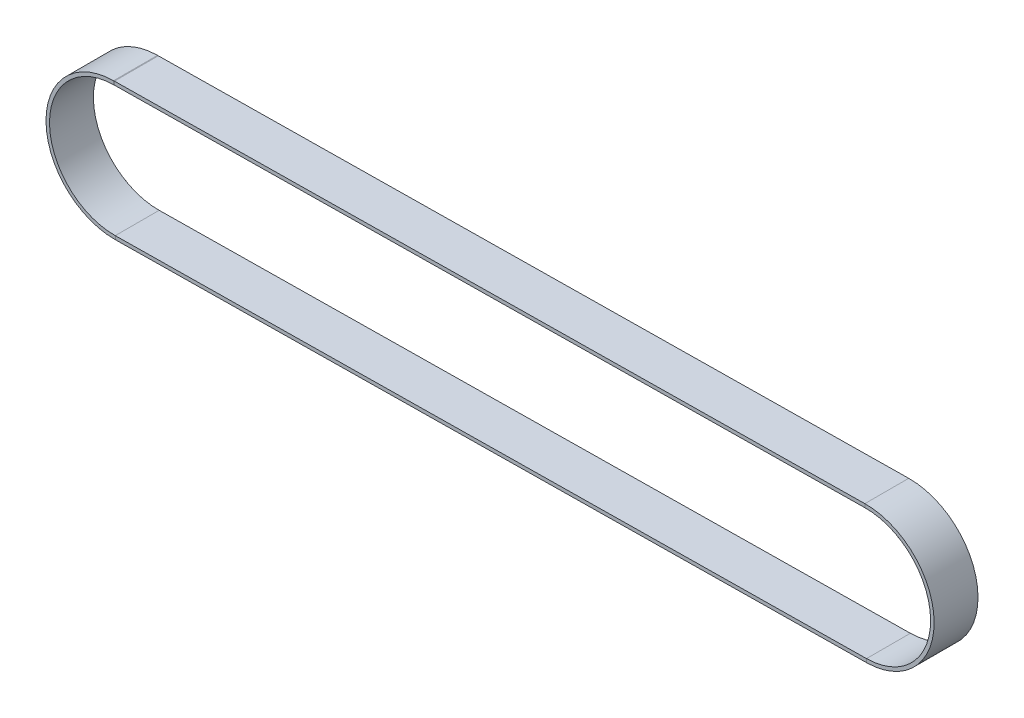
SolidWorks part; units mm, degrees
ref_plane "Front Plane" through (0, 0, 0) normal (0, 0, 1) x (1, 0, 0)
ref_plane "Top Plane" through (0, 0, 0) normal (0, 1, 0) x (1, 0, 0)
ref_plane "Right Plane" through (0, 0, 0) normal (1, 0, 0) x (0, 0, -1)
sketch "Sketch2" plane through (0, 0, 0) normal (0, 0, 1) x (1, 0, 0)
  line L0 (0, 0) -> (1, 0) construction
  line L1 (0, 0) -> (0, 1) construction
  line L2 (-0.4713, 37.9971) -> (427.4958, 43.3052)
  line L3 (428.4384, -32.6889) -> (0.4713, -37.9971)
  arc A0 (0.4713, -37.9971) -> (-0.4713, 37.9971) centre (0, 0) cw
  arc A1 (427.4958, 43.3052) -> (428.4384, -32.6889) centre (427.9671, 5.3081) cw
sketch "Sketch3" plane through (0, 0, 0) normal (1, 0, 0) x (0, 0, -1)
  line L0 (0, 43.3081) -> (0, -32.6889) construction
  line L1 (-12.5, 38.9971) -> (12.5, 38.9971)
  line L2 (-12.5, 38.9971) -> (-12.5, 36.9971)
  line L3 (-12.5, 36.9971) -> (12.5, 36.9971)
  line L4 (12.5, 38.9971) -> (12.5, 36.9971)
  line L5 (-12.5, 38.9971) -> (12.5, 36.9971) construction
  line L6 (-12.5, 36.9971) -> (12.5, 38.9971) construction
  line L7 (0, 37.9971) -> (0, 43.3052) construction
  point P0 (0, 37.9971)
  dimension "D1" = 25
  dimension "D2" = 2
sweep "Sweep2" add profiles "Sketch3" path "Sketch2"
